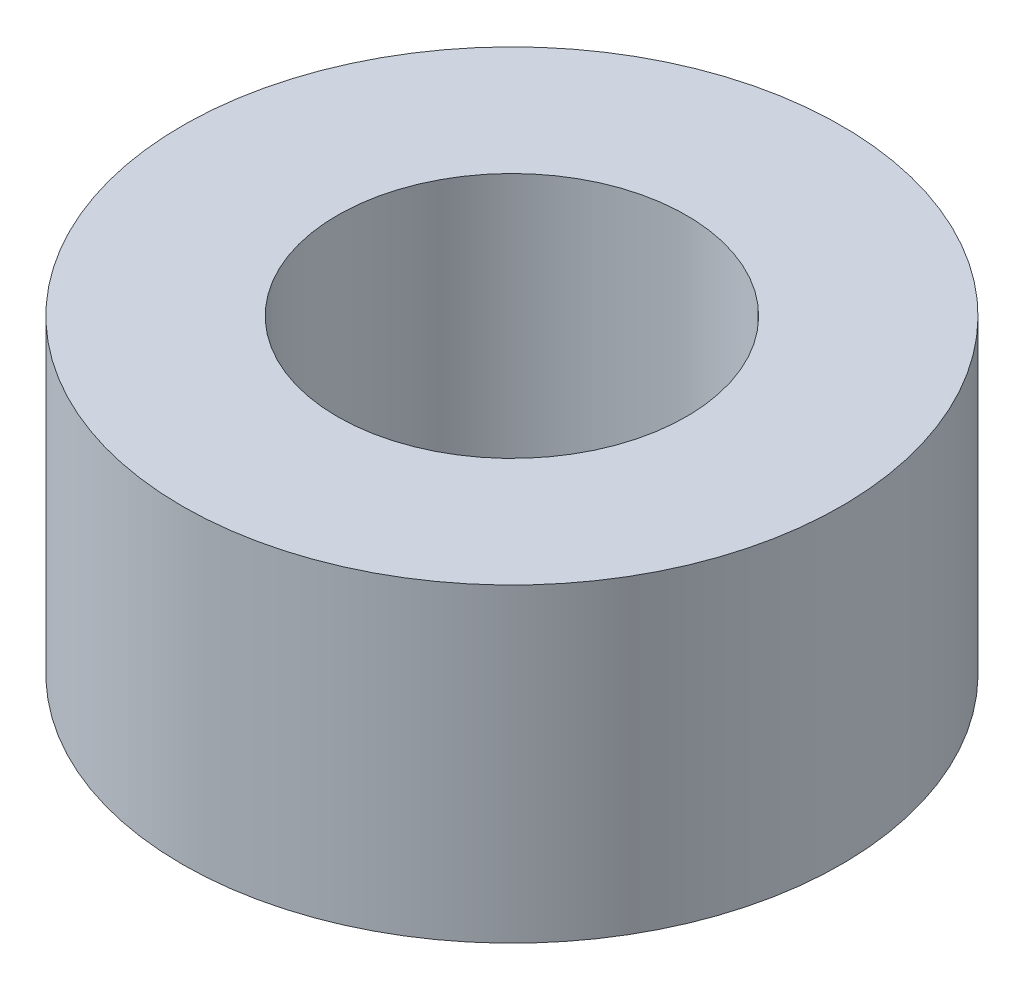
SolidWorks part; units mm, degrees
ref_plane "Front Plane" through (0, 0, 0) normal (0, 0, 1) x (1, 0, 0)
ref_plane "Top Plane" through (0, 0, 0) normal (0, 1, 0) x (1, 0, 0)
ref_plane "Right Plane" through (0, 0, 0) normal (1, 0, 0) x (0, 0, -1)
sketch "Sketch1" plane through (0, 0, 0) normal (0, 1, 0) x (1, 0, 0)
  circle A0 centre (0, 0) radius 2.25
  circle A2 centre (0, 0) radius 4.25
  dimension "D1" = 4.5
  dimension "D2" = 2
extrude "Boss-Extrude1" add sketch "Sketch1" along normal blind 4
